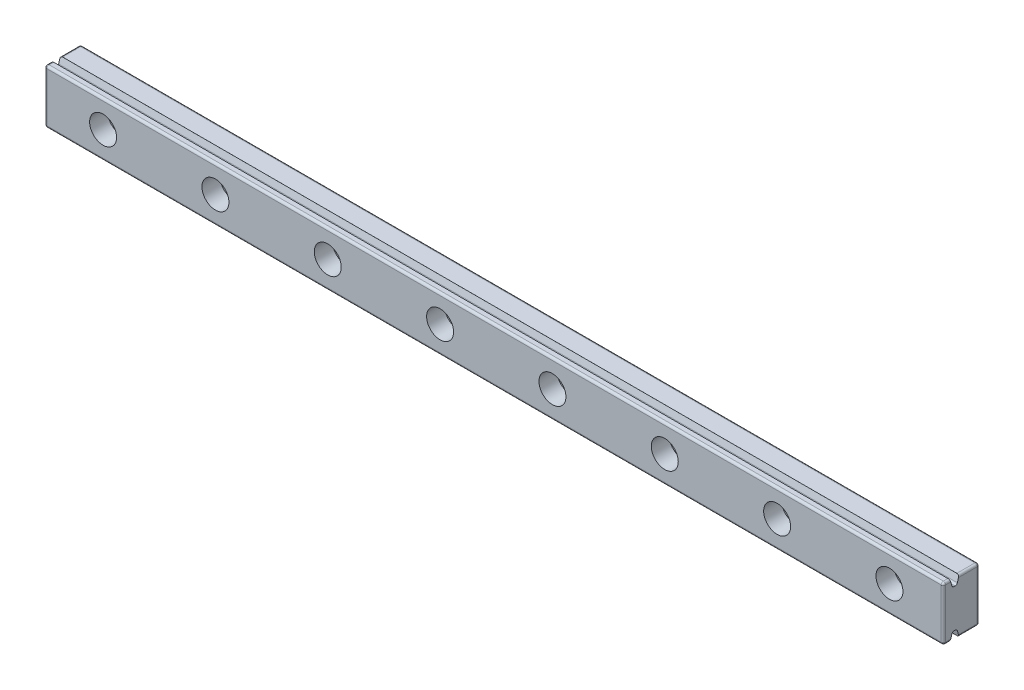
SolidWorks part; units mm, degrees
other "Markup1"
sketch "Sketch4" plane through (450, 6, 4) normal (0.5774, 0.5773, 0.5774) x (0.7071, 0, -0.7071)
ref_plane "Front Plane" through (0, 0, 0) normal (0, 0, 1) x (1, 0, 0)
ref_plane "Top Plane" through (0, 0, 0) normal (0, 1, 0) x (1, 0, 0)
ref_plane "Right Plane" through (0, 0, 0) normal (1, 0, 0) x (0, 0, -1)
sketch "Sketch1" plane through (0, 0, 0) normal (1, 0, 0) x (0, 0, -1)
  line L0 (-0.5, 6) -> (4, 6)
  line L1 (-4, 6) -> (-2.5, 6)
  line L2 (-4, 6) -> (-4, -6)
  line L3 (-4, -6) -> (-2.5, -6)
  line L4 (4, 6) -> (4, -6)
  line L5 (-4, 6) -> (4, -6) construction
  line L6 (-4, -6) -> (4, 6) construction
  line L8 (-2.5, 6) -> (-2.5, 4.25)
  line L9 (-2.5, 4.25) -> (-0.5, 4.25)
  line L10 (-0.5, 6) -> (-0.5, 4.25)
  line L12 (-2.5, -6) -> (-2.5, -4.25)
  line L13 (-2.5, -4.25) -> (-0.5, -4.25)
  line L14 (-0.5, -6) -> (-0.5, -4.25)
  line L15 (-0.5, -6) -> (4, -6)
  point P0 (0, 0)
  dimension "D1" = 12
  dimension "D2" = 8
  dimension "D3" = 2
  dimension "D4" = 2
  dimension "D5" = 1.5
  dimension "D6" = 1.5
  dimension "D7" = 8.5
  dimension "D8" = 4.25
extrude "Boss-Extrude1" add sketch "Sketch1" along normal blind 200
sketch "Sketch2" plane through (0, 0, 4) normal (0, 0, 1) x (1, 0, 0)
  line L0 (0, 6) -> (0, -6) construction
  circle A0 centre (13, 0) radius 1.75
  circle A1 centre (38, 0) radius 1.75
  circle A2 centre (63, 0) radius 1.75
  circle A3 centre (88, 0) radius 1.75
  circle A4 centre (113, 0) radius 1.75
  circle A5 centre (138, 0) radius 1.75
  circle A6 centre (163, 0) radius 1.75
  circle A7 centre (188, 0) radius 1.75
  circle A8 centre (213, 0) radius 1.75
  circle A9 centre (238, 0) radius 1.75
  circle A10 centre (263, 0) radius 1.75
  circle A11 centre (288, 0) radius 1.75
  circle A12 centre (313, 0) radius 1.75
  circle A13 centre (338, 0) radius 1.75
  circle A14 centre (363, 0) radius 1.75
  circle A15 centre (388, 0) radius 1.75
  circle A16 centre (413, 0) radius 1.75
  circle A17 centre (438, 0) radius 1.75
  dimension "D1" = 3.5
  dimension "D2" = 13
  dimension "D3" = 18
extrude "Cut-Extrude1" cut sketch "Sketch2" against normal blind 10
sketch "Sketch3" plane through (0, 0, 4) normal (0, 0, 1) x (1, 0, 0)
  circle A0 centre (13, 0) radius 3
  circle A1 centre (38, 0) radius 3
  circle A2 centre (63, 0) radius 3
  circle A3 centre (88, 0) radius 3
  circle A4 centre (113, 0) radius 3
  circle A5 centre (138, 0) radius 3
  circle A6 centre (163, 0) radius 3
  circle A7 centre (188, 0) radius 3
  circle A8 centre (213, 0) radius 3
  circle A9 centre (238, 0) radius 3
  circle A10 centre (263, 0) radius 3
  circle A11 centre (288, 0) radius 3
  circle A12 centre (313, 0) radius 3
  circle A13 centre (338, 0) radius 3
  circle A14 centre (363, 0) radius 3
  circle A15 centre (388, 0) radius 3
  circle A16 centre (413, 0) radius 3
  circle A17 centre (438, 0) radius 3
  dimension "D1" = 6
  dimension "D2" = 18
extrude "Cut-Extrude2" cut sketch "Sketch3" against normal blind 4
chamfer "Chamfer1" distance 0.5 angle 74 4 edges at (100, -4.25, 2.5) (100, -4.25, 0.5) (100, 4.25, 2.5) (100, 4.25, 0.5)
fillet "Fillet1" radius 0.5 20 edges at (200, -6, -1.75) (200, 0, -4) (200, 6, -1.75) (200, 6, 3.25) (200, 0, 4) (200, -6, 3.25) (0, -6, 3.25) (0, -6, -1.75) (0, 0, -4) (0, 6, -1.75) (0, 6, 3.25) (0, 0, 4) (100, -4.25, 1) (100, -4.25, 2) (100, 4.25, 2) (100, 4.25, 1) (100, -6, 4) (100, 6, 4) (100, -6, -4) (100, 6, -4)
